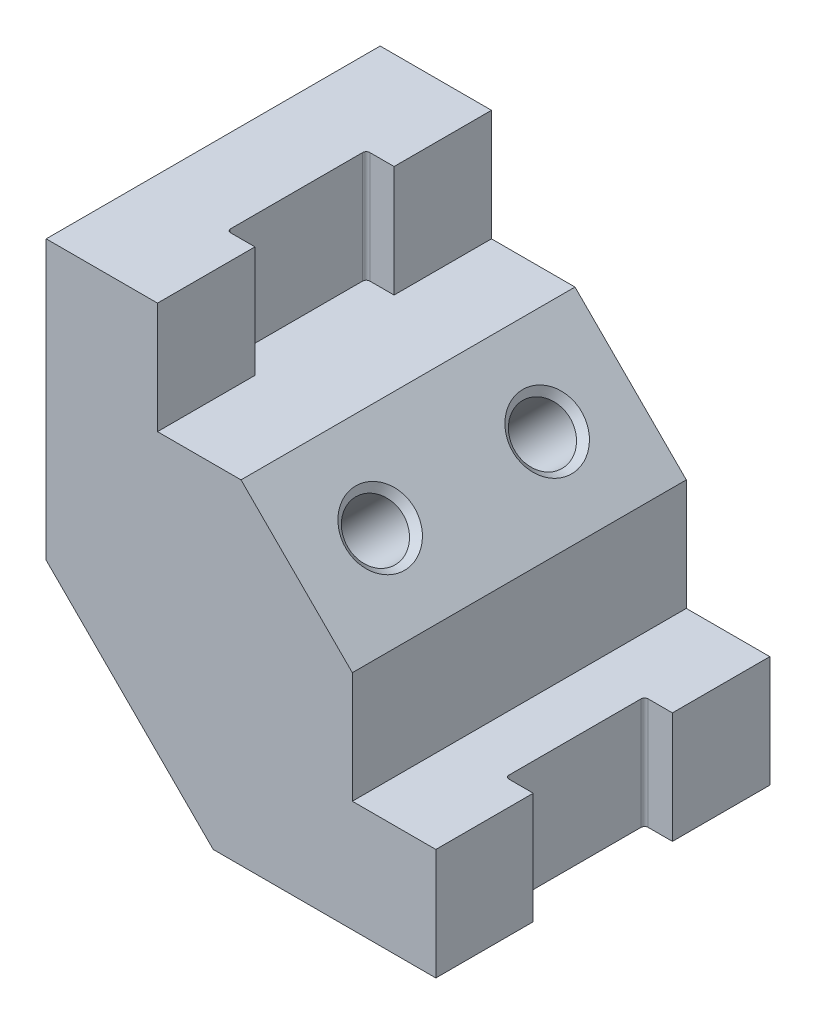
SolidWorks part; units mm, degrees
ref_plane "Front Plane" through (0, 0, 0) normal (0, 0, 1) x (1, 0, 0)
ref_plane "Top Plane" through (0, 0, 0) normal (0, 1, 0) x (1, 0, 0)
ref_plane "Right Plane" through (0, 0, 0) normal (1, 0, 0) x (0, 0, -1)
sketch "Sketch2" plane through (0, 0, 0) normal (0, 0, 1) x (1, 0, 0)
  line L0 (-62.5672, 49.0062) -> (-62.5672, -14.4938)
  line L1 (-24.4672, -52.5938) -> (26.3328, -52.5938)
  line L2 (26.3328, -52.5938) -> (26.3328, -27.1938)
  line L3 (26.3328, -27.1938) -> (7.2828, -27.1938)
  line L4 (7.2828, -27.1938) -> (7.2828, -1.7938)
  line L5 (7.2828, -1.7938) -> (-18.1172, 23.6062)
  line L6 (-18.1172, 23.6062) -> (-37.1672, 23.6062)
  line L7 (-37.1672, 23.6062) -> (-37.1672, 49.0062)
  line L8 (-37.1672, 49.0062) -> (-62.5672, 49.0062)
  line L9 (-24.4672, -52.5938) -> (-62.5672, -14.4938)
  point P1 (-49.8672, 49.0062)
  dimension "D1" = 101.6
  dimension "D2" = 88.9
  dimension "D3" = 25.4
  dimension "D4" = 44.45
  dimension "D5" = 50.8
  dimension "D6" = 76.2
  dimension "D7" = 38.1
  dimension "D8" = 45
  dimension "D9" = 45
extrude "Boss-Extrude1" add sketch "Sketch2" against normal blind 76.2
sketch "Sketch3" plane through (2.7445, 2.7445, 0) normal (0.7071, 0.7071, 0) x (0, 0, -1)
  line L0 (38.1, 78.8943) -> (38.1, -55.8095) construction
  line L1 (76.2, 78.8943) -> (0, 78.8943) construction
  line L2 (76.2, -55.8095) -> (0, -55.8095) construction
  point P6 (0, 0)
sketch "Sketch4" plane through (26.3328, 0, 0) normal (1, 0, 0) x (0, 0, -1)
  line L0 (76.2, -27.1938) -> (0, -27.1938) construction
  line L1 (22.225, -27.1938) -> (53.975, -27.1938)
  line L2 (22.225, -27.1938) -> (22.225, -33.5438)
  line L3 (22.225, -33.5438) -> (53.975, -33.5438)
  line L4 (53.975, -27.1938) -> (53.975, -33.5438)
  line L5 (0, -52.5938) -> (0, -27.1938) construction
  dimension "D1" = 31.75
  dimension "D2" = 6.35
  dimension "D3" = 22.225
sketch "Sketch6" plane through (0, 49.0062, 0) normal (0, 1, 0) x (1, 0, 0)
  line L0 (-37.1672, 76.2) -> (-37.1672, 0) construction
  line L1 (-37.1672, 53.975) -> (-43.5172, 53.975)
  line L2 (-37.1672, 53.975) -> (-37.1672, 22.225)
  line L3 (-37.1672, 22.225) -> (-43.5172, 22.225)
  line L4 (-43.5172, 53.975) -> (-43.5172, 22.225)
  line L5 (-37.1672, 76.2) -> (-62.5672, 76.2) construction
  dimension "D1" = 6.35
  dimension "D2" = 31.75
  dimension "D3" = 22.225
extrude "Cut-Extrude2" cut sketch "Sketch6" against normal up to surface (25.4 mm away) up to face at (-27.6422, 23.6062, -38.1)
fillet "Fillet2" radius 0.8128 2 edges at (-43.5172, 36.3062, -22.225) (-43.5172, 36.3062, -53.975)
sketch "Sketch7" plane through (2.7445, 2.7445, 0) normal (0.7071, 0.7071, 0) x (0, 0, -1)
  line L1 (76.2, -6.4181) -> (0, -6.4181) construction
  line L2 (38.1, 78.8943) -> (38.1, -55.8095) construction
  circle A0 centre (57.15, 11.5397) radius 6.35
  circle A1 centre (19.05, 11.5397) radius 6.35
  dimension "D4" = 12.7
  dimension "D2" = 17.9578
  dimension "D3" = 19.05
  dimension "D1" = 2
extrude "Cut-Extrude3" cut sketch "Sketch7" against normal blind 76.2 contours A1 | A0
chamfer "Chamfer1" distance 1.524 angle 45 2 edges at (-9.9054, 15.3944, -57.15) (-9.9054, 15.3944, -19.05)
sketch "Sketch8" plane through (0, -27.1938, 0) normal (0, 1, 0) x (1, 0, 0)
  line L0 (26.3328, 76.2) -> (26.3328, 0) construction
  line L1 (26.3328, 53.975) -> (19.9828, 53.975)
  line L2 (26.3328, 53.975) -> (26.3328, 22.225)
  line L3 (26.3328, 22.225) -> (19.9828, 22.225)
  line L4 (19.9828, 53.975) -> (19.9828, 22.225)
  line L5 (26.3328, 76.2) -> (7.2828, 76.2) construction
  dimension "D1" = 6.35
  dimension "D2" = 31.75
  dimension "D3" = 22.225
extrude "Cut-Extrude4" cut sketch "Sketch8" against normal through all
fillet "Fillet3" radius 0.8128 2 edges at (19.9828, -39.8938, -22.225) (19.9828, -39.8938, -53.975)
